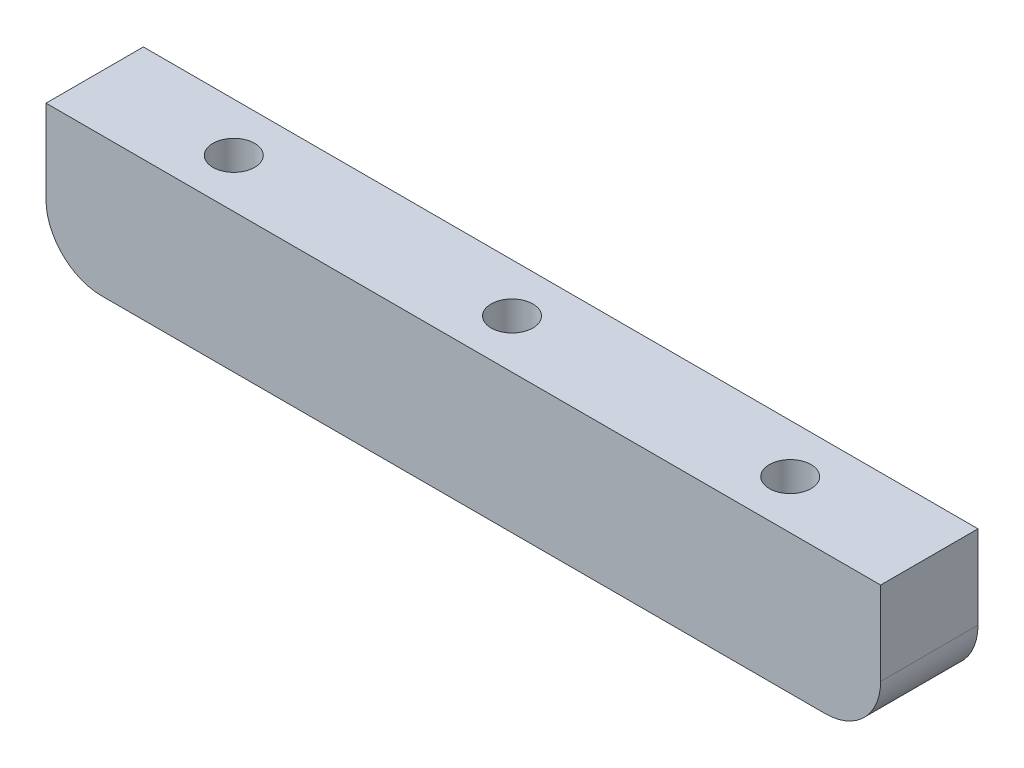
SolidWorks part; units mm, degrees
ref_plane "Front Plane" through (0, 0, 0) normal (0, 0, 1) x (1, 0, 0)
ref_plane "Top Plane" through (0, 0, 0) normal (0, 1, 0) x (1, 0, 0)
ref_plane "Right Plane" through (0, 0, 0) normal (1, 0, 0) x (0, 0, -1)
sketch "Sketch1" plane through (0, 0, 0) normal (0, 1, 0) x (1, 0, 0)
  line L1 (-30, 3.5) -> (30, 3.5)
  line L2 (-30, 3.5) -> (-30, -3.5)
  line L3 (-30, -3.5) -> (30, -3.5)
  line L4 (30, 3.5) -> (30, -3.5)
  line L5 (-30, 3.5) -> (30, -3.5) construction
  line L6 (-30, -3.5) -> (30, 3.5) construction
  point P0 (0, 0)
  dimension "D1" = 60
  dimension "D2" = 7
extrude "Boss-Extrude1" add sketch "Sketch1" along normal blind 10
sketch "Sketch2" plane through (0, 10, 0) normal (0, 1, 0) x (1, 0, 0)
  line L0 (0, 3.5) -> (0, -3.5) construction
  line L1 (30, 3.5) -> (-30, 3.5) construction
  line L2 (-30, -3.5) -> (30, -3.5) construction
  line L3 (-30, 0) -> (30, 0) construction
  line L4 (-30, 3.5) -> (-30, -3.5) construction
  line L5 (30, -3.5) -> (30, 3.5) construction
  circle A0 centre (0, 0) radius 1.5
  circle A1 centre (20, 0) radius 1.5
  circle A2 centre (-20, 0) radius 1.5
  dimension "D1" = 3
  dimension "D2" = 20
  dimension "D3" = 20
extrude "Cut-Extrude1" cut sketch "Sketch2" against normal blind 5
fillet "Fillet1" radius 4 2 edges at (-30, 0, 0) (30, 0, 0)
equation "\"D3@Sketch2\"=\"D2@Sketch2\""
